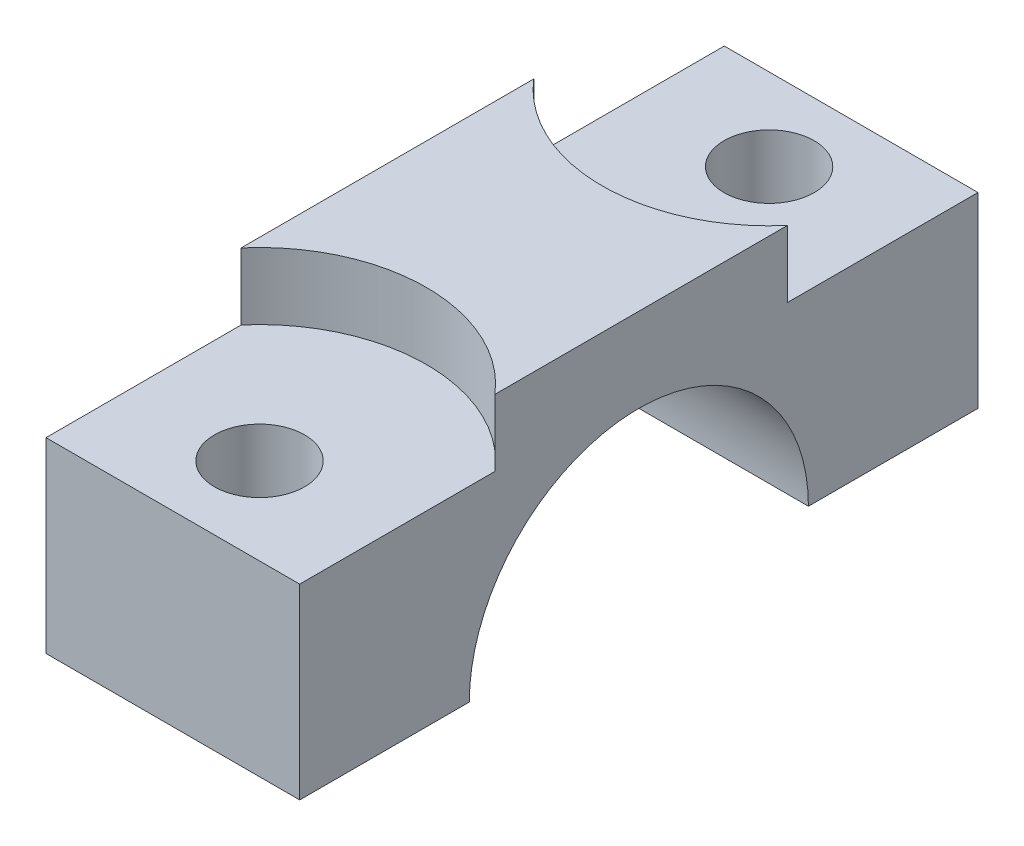
SolidWorks part; units mm, degrees
ref_plane "Front Plane" through (0, 0, 0) normal (0, 0, 1) x (1, 0, 0)
ref_plane "Top Plane" through (0, 0, 0) normal (0, 1, 0) x (1, 0, 0)
ref_plane "Right Plane" through (0, 0, 0) normal (1, 0, 0) x (0, 0, -1)
sketch "Sketch1" plane through (0, 0, 0) normal (1, 0, 0) x (0, 0, -1)
  line L0 (12.7, 0) -> (25.4, 0)
  line L1 (-25.4, 19) -> (25.4, 19)
  line L2 (-25.4, 19) -> (-25.4, 0)
  line L3 (-25.4, 0) -> (-12.7, 0)
  line L4 (25.4, 19) -> (25.4, 0)
  arc A0 (-12.7, 0) -> (12.7, 0) centre (0, 0) cw
  point P8 (0, 0)
  point P9 (0, 0)
  point P10 (0, 19)
  dimension "D3" = 12.7
  dimension "D1" = 50.8
  dimension "D2" = 19
extrude "Boss-Extrude1" add sketch "Sketch1" along normal mid plane 19
sketch "Sketch2" plane through (0, 0, 0) normal (0, -1, 0) x (1, 0, 0)
  line L0 (-9.5, 19.05) -> (9.5, 19.05) construction
  line L1 (-9.5, 25.4) -> (-9.5, 12.7) construction
  line L2 (9.5, 25.4) -> (9.5, 12.7) construction
  line L3 (-9.5, -19.05) -> (9.5, -19.05) construction
  line L4 (-9.5, -12.7) -> (-9.5, -25.4) construction
  line L5 (9.5, -12.7) -> (9.5, -25.4) construction
  point P12 (0, 19.05)
  point P13 (0, -19.05)
hole_wizard "CBORE for M12 Hex Head Cap Screw1" positions "Sketch3" profile "Sketch4" counterbore size "M12" standard "ISO"
sketch "Sketch3" plane through (0, 19, 0) normal (0, 1, 0) x (1, 0, 0)
  point P0 (0, 19.2545)
  point P2 (0, -18.9082)
sketch "Sketch4" plane through (0, 19, -19.2545) normal (1, 0, 0) x (0, 0, 1)
  line L0 (0, 0) -> (0, 18.5379)
  line L1 (0, 18.5379) -> (3.375, 16.51)
  line L2 (3.375, 16.51) -> (3.375, 5)
  line L3 (3.375, 5) -> (12.5, 5)
  line L4 (12.5, 5) -> (12.5, 0)
  line L5 (12.5, 0) -> (0, 0)
  line L10 (0, 18.5379) -> (-3.375, 16.51) construction
  line L11 (0, -6.35) -> (0, 107.95) construction
  dimension "Hole Dia." = 6.75
  dimension "Hole Depth" = 16.51
  dimension "C'Bore Dia." = 25
  dimension "C'Bore Depth" = 5
  dimension "Drill Angle" = 118
